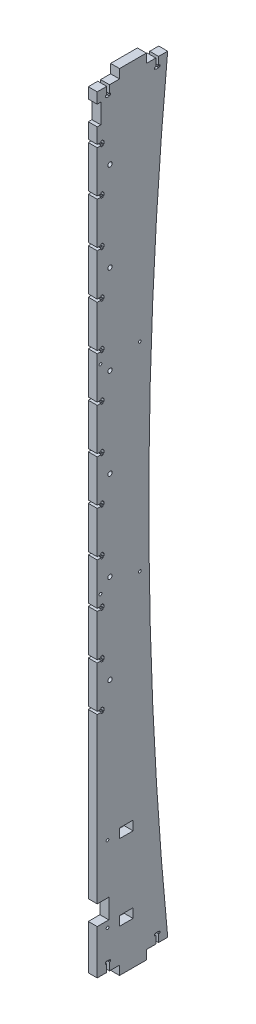
SolidWorks part; units mm, degrees
ref_plane "Płaszczyzna przednia" through (0, 0, 0) normal (0, 0, 1) x (1, 0, 0)
ref_plane "Płaszczyzna górna" through (0, 0, 0) normal (0, 1, 0) x (1, 0, 0)
ref_plane "Płaszczyzna prawa" through (0, 0, 0) normal (1, 0, 0) x (0, 0, -1)
ref_plane "Płaszczyzna2" through (248.5228, 0, 0) normal (-1, 0, 0) x (0, 0, 1)
sketch "Szkic11" plane through (248.5228, 0, 0) normal (-1, 0, 0) x (0, 0, 1)
  line L0 (-79.0014, 0) -> (0, 0)
  line L1 (0, 880) -> (-78.9552, 880)
  line L2 (-78.9552, 870) -> (-78.9552, 880)
  line L4 (-79.0014, 10) -> (-79.0014, 0)
  line L13 (0, 0) -> (0, 880)
  arc A2 (-79.0014, 10) -> (-78.9552, 870) centre (-4437.8003, 440.2341) ccw
extrude "Dodanie-wyciągnięcie1" add sketch "Szkic11" along normal blind 10
sketch "Szkic1" plane through (248.5228, 0, 0) normal (1, 0, 0) x (0, 0, -1)
  line L0 (85, 880) -> (85, 869.9)
  line L1 (85, 880) -> (55, 880)
  line L2 (85, 869.9) -> (55, 869.9)
  line L3 (55, 880) -> (55, 869.9)
  line L5 (25, 880) -> (25, 869.9)
  line L6 (25, 880) -> (0, 880)
  line L7 (25, 869.9) -> (0, 869.9)
  line L8 (0, 880) -> (0, 869.9)
  line L9 (0, 880) -> (78.9552, 880) construction
  dimension "D1" = 25
  dimension "D2" = 30
  dimension "D3" = 30
  dimension "D4" = 10.1
  dimension "D5" = 10.1
  dimension "D6" = 0
extrude "Wytnij-wyciągnięcie1" cut sketch "Szkic1" against normal blind 10
sketch "Szkic2" plane through (248.5228, 0, 0) normal (1, 0, 0) x (0, 0, -1)
  line L0 (10.6609, 869.9) -> (13.7609, 869.9)
  line L1 (10.6609, 869.9) -> (10.6609, 861.4)
  line L2 (13.7609, 869.9) -> (13.7609, 861.4)
  line L3 (10.6609, 858.9) -> (13.7609, 858.9)
  line L5 (9.2859, 859.4) -> (10.6609, 859.4)
  line L6 (9.2859, 859.4) -> (9.2859, 861.4)
  line L7 (15.1359, 859.4) -> (15.1359, 861.4)
  line L8 (9.2859, 861.4) -> (10.6609, 861.4)
  line L9 (13.7609, 859.4) -> (15.1359, 859.4)
  line L10 (10.6609, 859.4) -> (10.6609, 858.9)
  line L11 (13.7609, 859.4) -> (13.7609, 858.9)
  line L12 (13.7609, 861.4) -> (15.1359, 861.4)
  line L13 (0, 869.9) -> (25, 869.9) construction
  dimension "D1" = 11
  dimension "D2" = 5.85
  dimension "D3" = 3.1
  dimension "D4" = 1.375
  dimension "D5" = 2
  dimension "D6" = 0.5
  dimension "D7" = 0
extrude "Wytnij-wyciągnięcie2" cut sketch "Szkic2" against normal blind 10
pattern_linear "Szyk liniowy1" count 2 spacing 55 along (0, 0, -1) of "Wytnij-wyciągnięcie2"
ref_plane "Płaszczyzna1" through (0, 440, 0) normal (0, 1, 0) x (1, 0, 0)
sketch "Szkic4" plane through (248.5228, 0, 0) normal (-1, 0, 0) x (0, 0, 1)
  line L0 (-40, 143) -> (-25, 143) construction
  line L1 (-25, 143) -> (-25, 133) construction
  line L2 (-40, 133) -> (-25, 133) construction
  line L3 (-40, 143) -> (-40, 133) construction
  line L4 (-40, 48) -> (-25, 48) construction
  line L5 (-25, 58) -> (-25, 48) construction
  line L6 (-40, 58) -> (-25, 58) construction
  line L7 (-40, 58) -> (-40, 48) construction
  line L8 (-40, 143) -> (-25, 143)
  line L9 (-25, 143) -> (-25, 133)
  line L10 (-40, 133) -> (-25, 133)
  line L11 (-40, 143) -> (-40, 133)
  line L12 (-40, 48) -> (-25, 48)
  line L13 (-25, 58) -> (-25, 48)
  line L14 (-40, 58) -> (-25, 58)
  line L15 (-40, 58) -> (-40, 48)
  line L16 (-40.2, 132.8) -> (-24.8, 132.8)
  line L17 (-24.8, 143.2) -> (-24.8, 132.8)
  line L18 (-40.2, 143.2) -> (-24.8, 143.2)
  line L19 (-40.2, 143.2) -> (-40.2, 132.8)
  line L20 (-40.2, 47.8) -> (-24.8, 47.8)
  line L21 (-24.8, 58.2) -> (-24.8, 47.8)
  line L22 (-40.2, 58.2) -> (-24.8, 58.2)
  line L23 (-40.2, 58.2) -> (-40.2, 47.8)
  line L24 (-10, 58) -> (-10, 48) construction
  line L25 (-13.1, 58) -> (-13.1, 48) construction
  line L26 (-10, 143) -> (-10, 133) construction
  line L27 (-13.1, 143) -> (-13.1, 133) construction
  line L28 (-10, 58) -> (-10, 48)
  line L29 (-13.1, 58) -> (-13.1, 48)
  line L30 (-10, 143) -> (-10, 133)
  line L31 (-13.1, 143) -> (-13.1, 133)
  line L32 (-10, 138) -> (-13.1, 138)
  line L33 (-10, 53) -> (-13.1, 53)
  circle A0 centre (-11.55, 53) radius 1.55
  circle A1 centre (-11.55, 138) radius 1.55
  dimension "D2" = 3.1
  dimension "D3" = 3.1
  dimension "D1" = 0.2
sketch "Szkic5" plane through (248.5228, 0, 0) normal (-1, 0, 0) x (0, 0, 1)
  line L0 (-40.2, 132.8) -> (-24.8, 132.8) construction
  line L1 (-24.8, 143.2) -> (-24.8, 132.8) construction
  line L2 (-40.2, 143.2) -> (-24.8, 143.2) construction
  line L3 (-40.2, 143.2) -> (-40.2, 132.8) construction
  line L4 (-40.2, 47.8) -> (-24.8, 47.8) construction
  line L5 (-24.8, 58.2) -> (-24.8, 47.8) construction
  line L6 (-40.2, 58.2) -> (-24.8, 58.2) construction
  line L7 (-40.2, 58.2) -> (-40.2, 47.8) construction
  line L8 (-40.2, 132.8) -> (-24.8, 132.8)
  line L9 (-24.8, 143.2) -> (-24.8, 132.8)
  line L10 (-40.2, 143.2) -> (-24.8, 143.2)
  line L11 (-40.2, 143.2) -> (-40.2, 132.8)
  line L12 (-40.2, 47.8) -> (-24.8, 47.8)
  line L13 (-24.8, 58.2) -> (-24.8, 47.8)
  line L14 (-40.2, 58.2) -> (-24.8, 58.2)
  line L15 (-40.2, 58.2) -> (-40.2, 47.8)
  circle A0 centre (-11.55, 53) radius 1.55 construction
  circle A1 centre (-11.55, 138) radius 1.55 construction
  circle A2 centre (-11.55, 53) radius 1.55
  circle A3 centre (-11.55, 138) radius 1.55
extrude "Wytnij-wyciągnięcie3" cut sketch "Szkic5" along normal blind 10
sketch "Szkic6" plane through (248.5228, 0, 0) normal (1, 0, 0) x (0, 0, -1)
  line L1 (0, 815.69) -> (4.5, 815.69)
  line L2 (0, 815.69) -> (0, 818.79)
  line L3 (0, 818.79) -> (4.5, 818.79)
  line L4 (7.5, 815.69) -> (7.5, 818.79)
  line L5 (6.5, 815.69) -> (7.5, 815.69)
  line L6 (4.5, 814.315) -> (6.5, 814.315)
  line L7 (4.5, 814.315) -> (4.5, 815.69)
  line L8 (4.5, 820.165) -> (6.5, 820.165)
  line L9 (6.5, 814.315) -> (6.5, 815.69)
  line L10 (4.5, 818.79) -> (4.5, 820.165)
  line L11 (6.5, 818.79) -> (7.5, 818.79)
  line L12 (6.5, 818.79) -> (6.5, 820.165)
  line L14 (0, 869.9) -> (10.6609, 869.9) construction
  point P14 (0, 817.24)
  dimension "D1" = 7.5
  dimension "D2" = 1
  dimension "D3" = 2
  dimension "D4" = 5.85
  dimension "D5" = 1.375
  dimension "D6" = 3.1
  dimension "D7" = 52.66
extrude "Wytnij-wyciągnięcie4" cut sketch "Szkic6" against normal blind 10
pattern_linear "Szyk liniowy2" count 12 spacing 50 along (0, -1, 0) of "Wytnij-wyciągnięcie4"
sketch "Szkic7" plane through (248.5228, 0, 0) normal (1, 0, 0) x (0, 0, -1)
  circle A0 centre (14.3107, 792.237) radius 3.2 construction
  circle A1 centre (14.3107, 792.237) radius 3.2
  circle A2 centre (14.3107, 792.237) radius 2.45
  dimension "D1" = 4.9
sketch "Szkic8" plane through (248.5228, 0, 0) normal (1, 0, 0) x (0, 0, -1)
  line L3 (13, 60) -> (13, 82)
  line L4 (0, 60) -> (13, 60)
  line L5 (13, 82) -> (0, 82)
  line L6 (0, 60) -> (0, 82)
extrude "Wytnij-wyciągnięcie6" cut sketch "Szkic8" against normal blind 10
sketch "Szkic9" plane through (248.5228, 0, 0) normal (1, 0, 0) x (0, 0, -1)
  line L0 (0, 869.9) -> (10.6609, 869.9) construction
  line L1 (0, 835.9) -> (0, 857.9)
  line L2 (0, 835.9) -> (4, 835.9)
  line L3 (0, 857.9) -> (4, 857.9)
  line L4 (4, 835.9) -> (4, 857.9)
  dimension "D1" = 22
  dimension "D2" = 4
  dimension "D3" = 12
extrude "Wytnij-wyciągnięcie7" cut sketch "Szkic9" against normal blind 10
mirror "Lustro1" about plane through (0, 440, 0) normal (0, 1, 0) of "Szyk liniowy1", "Wytnij-wyciągnięcie2", "Wytnij-wyciągnięcie1"
sketch "Szkic12" plane through (248.5228, 0, 0) normal (1, 0, 0) x (0, 0, -1)
  line L0 (2.15, 600.737) -> (2.15, 606.737) construction
  line L1 (5.25, 600.737) -> (5.25, 606.737) construction
  line L2 (46.15, 600.737) -> (46.15, 606.737) construction
  line L3 (49.25, 600.737) -> (49.25, 606.737) construction
  line L4 (2.15, 600.737) -> (2.15, 606.737)
  line L5 (5.25, 600.737) -> (5.25, 606.737)
  line L6 (46.15, 600.737) -> (46.15, 606.737)
  line L7 (49.25, 600.737) -> (49.25, 606.737)
  line L8 (2.15, 603.737) -> (5.25, 603.737)
  line L9 (49.25, 603.737) -> (46.15, 603.737)
  circle A0 centre (3.7, 603.737) radius 1.55
  circle A1 centre (47.7, 603.737) radius 1.55
  dimension "D1" = 3.1
  dimension "D2" = 3.1
sketch "Szkic13" plane through (248.5228, 0, 0) normal (1, 0, 0) x (0, 0, -1)
  circle A0 centre (3.7, 603.737) radius 1.55 construction
  circle A1 centre (47.7, 603.737) radius 1.55 construction
  circle A2 centre (3.7, 603.737) radius 1.55
  circle A3 centre (47.7, 603.737) radius 1.55
extrude "Wytnij-wyciągnięcie8" cut sketch "Szkic13" against normal blind 10
pattern_linear "Szyk liniowy4" count 2 spacing 223 along (0, -1, 0) of "Wytnij-wyciągnięcie8"
sketch "Szkic14" plane through (248.5228, 0, 0) normal (1, 0, 0) x (0, 0, -1)
  circle A0 centre (14.3107, 792.237) radius 2.45 construction
  circle A1 centre (14.3107, 792.237) radius 2.45
extrude "Wytnij-wyciągnięcie9" cut sketch "Szkic14" against normal blind 10
pattern_linear "Szyk liniowy5" count 6 spacing 100 along (0, -1, 0) of "Wytnij-wyciągnięcie9"
equation "\"tolerancja_wpusy\"=0.2"
equation "\"dlugosc_wpustu_duzy\"=20"
equation "\"srednica_otworu_M3\"=3.1"
equation "\"szerokosc_nogi_T\"=3.1"
equation "\"dlugosc_T_30\"=11"
equation "\"grubosc_na_nakretke_kwadrat\"=2"
equation "\"szerokosc_na_nakretke_kwadrat\"=5.85"
equation "\"wyokosc_nadstawki_T\"=0.5"
equation "\"D1@Szkic2\"=\"dlugosc_T_30\""
equation "\"D2@Szkic2\"=\"szerokosc_na_nakretke_kwadrat\""
equation "\"D3@Szkic2\"=\"szerokosc_nogi_T\""
equation "\"D4@Szkic2\"=(\"szerokosc_na_nakretke_kwadrat\"-\"szerokosc_nogi_T\")/2"
equation "\"D5@Szkic2\"=\"grubosc_na_nakretke_kwadrat\""
equation "\"D6@Szkic2\"=\"wyokosc_nadstawki_T\""
equation "\"D2@Szkic4\"=\"srednica_otworu_M3\""
equation "\"D3@Szkic4\"=\"srednica_otworu_M3\""
equation "\"D3@Szkic6\"=\"grubosc_na_nakretke_kwadrat\""
equation "\"D4@Szkic6\"=\"szerokosc_na_nakretke_kwadrat\""
equation "\"D5@Szkic6\"=(\"szerokosc_na_nakretke_kwadrat\"-\"szerokosc_nogi_T\")/2"
equation "\"D6@Szkic6\"=\"szerokosc_nogi_T\""
equation "\"D1@Szkic12\"=\"srednica_otworu_M3\""
equation "\"D2@Szkic12\"=\"srednica_otworu_M3\""
